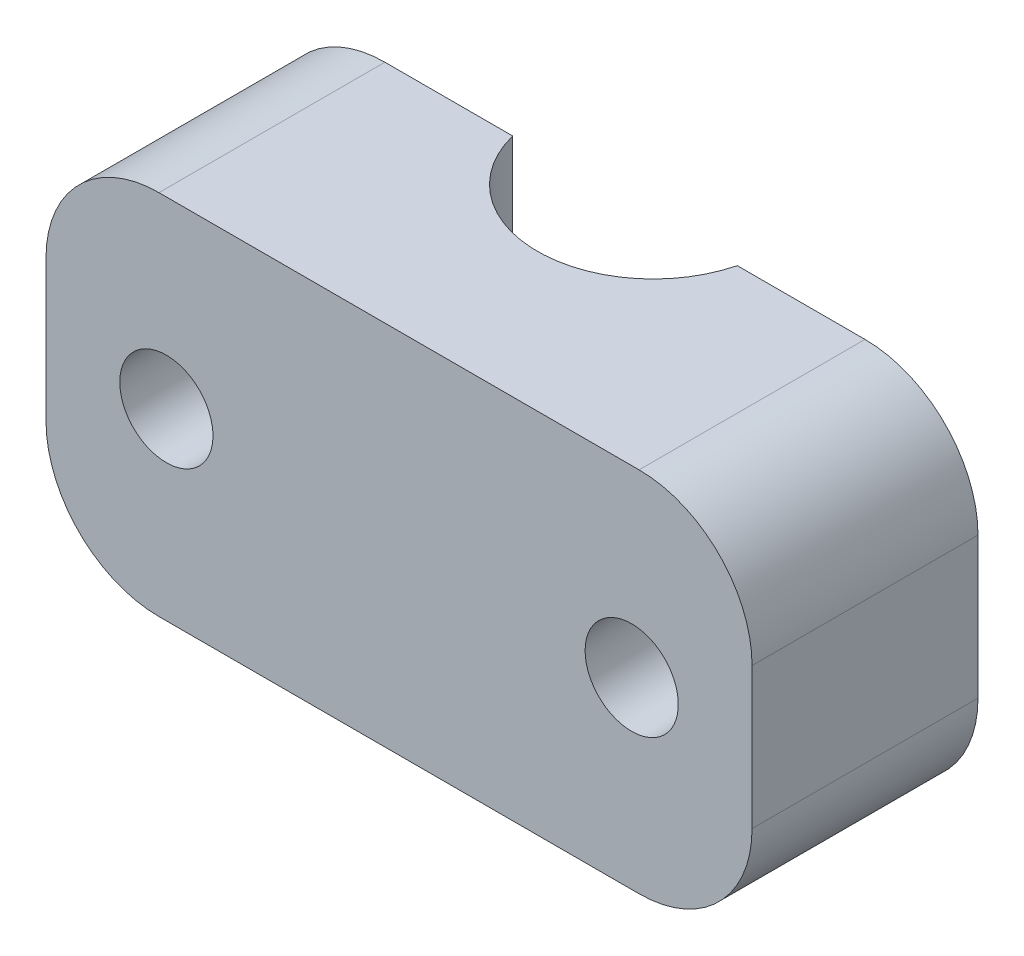
SolidWorks part; units mm, degrees
ref_plane "Front Plane" through (0, 0, 0) normal (0, 0, 1) x (1, 0, 0)
ref_plane "Top Plane" through (0, 0, 0) normal (0, 1, 0) x (1, 0, 0)
ref_plane "Right Plane" through (0, 0, 0) normal (1, 0, 0) x (0, 0, -1)
sketch "Sketch1" plane through (0, 0, 0) normal (0, 1, 0) x (1, 0, 0)
  line L1 (-12.5, -4) -> (12.5, -4)
  line L2 (-12.5, -4) -> (-12.5, 4)
  line L3 (-12.5, 4) -> (12.5, 4)
  line L4 (12.5, -4) -> (12.5, 4)
  line L5 (-12.5, -4) -> (12.5, 4) construction
  line L6 (-12.5, 4) -> (12.5, -4) construction
  point P0 (0, 0)
  dimension "D1" = 25
  dimension "D2" = 8
extrude "Boss-Extrude1" add sketch "Sketch1" along normal blind 13
sketch "Sketch2" plane through (0, 13, 0) normal (0, 1, 0) x (1, 0, 0)
  line L0 (12.5, 4) -> (-12.5, 4) construction
  line L1 (0, 5) -> (0, 0) construction
  circle A0 centre (0, 5) radius 4.1
  dimension "D1" = 8.2
  dimension "D2" = 1
extrude "Cut-Extrude1" cut sketch "Sketch2" against normal through all
sketch "Sketch3" plane through (0, 0, -4) normal (0, 0, -1) x (-1, 0, 0)
  line L0 (12.5, 0) -> (3.9762, 13) construction
  line L1 (-12.5, 0) -> (-3.9762, 13) construction
  circle A0 centre (8.2381, 6.5) radius 1.65
  circle A1 centre (-8.2381, 6.5) radius 1.65
  dimension "D1" = 3.3
extrude "Cut-Extrude2" cut sketch "Sketch3" against normal blind 10
fillet "Fillet2" radius 4 4 edges at (-12.5, 0, 0) (-12.5, 13, 0) (12.5, 13, 0) (12.5, 0, 0)
